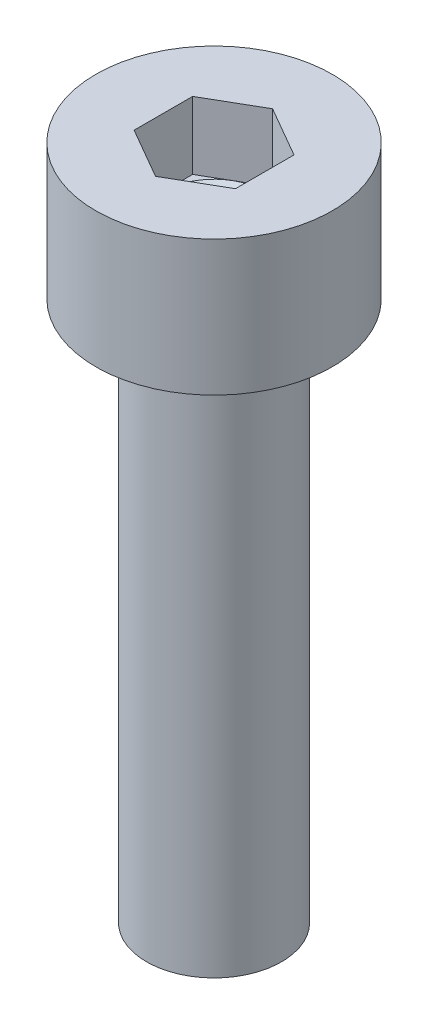
SolidWorks part; units mm, degrees
ref_plane "Front Plane" through (0, 0, 0) normal (0, 0, 1) x (1, 0, 0)
ref_plane "Top Plane" through (0, 0, 0) normal (0, 1, 0) x (1, 0, 0)
ref_plane "Right Plane" through (0, 0, 0) normal (1, 0, 0) x (0, 0, -1)
sketch "Sketch1" plane through (0, 0, 0) normal (0, 0, 1) x (1, 0, 0)
  line L0 (0, 0) -> (3.5, 0)
  line L1 (3.5, 0) -> (3.5, -4)
  line L2 (3.5, -4) -> (2, -4)
  line L3 (2, -4) -> (2, -20)
  line L4 (2, -20) -> (0, -20)
  line L5 (0, -20) -> (0, 0)
  line L7 (0, 0) -> (0, -20) construction
  dimension "CS_A" = 7
  dimension "CS_L" = 16
  dimension "CS_M" = 4
  dimension "CS_E" = 4
revolve "Revolve1" add sketch "Sketch1" angle 360 about L7
cosmetic thread "Cosmetic Thread1" parameters "CS_D_s"=3.242
sketch "Sketch2" plane through (0, 0, 0) normal (0, 0, 1) x (1, 0, 0)
  line L0 (1.5, 0) -> (1.5, -2)
  line L1 (1.5, -2) -> (0, -2.866)
  line L2 (0, -2.866) -> (0, 0)
  line L3 (0, 0) -> (1.5, 0)
  line L4 (0, 0) -> (0, -2.866) construction
  dimension "D1" = 60
  dimension "CS_B" = 3
  dimension "CS_T_s" = 2
revolve "Cut-Revolve1" cut sketch "Sketch2" angle 360 about L4
sketch "Sketch3" plane through (0, 0, 0) normal (0, 1, 0) x (1, 0, 0)
  line L1 (0, 1.7321) -> (-1.5, 0.866)
  line L2 (-1.5, 0.866) -> (-1.5, -0.866)
  line L3 (-1.5, -0.866) -> (0, -1.7321)
  line L4 (0, -1.7321) -> (1.5, -0.866)
  line L5 (1.5, -0.866) -> (1.5, 0.866)
  line L6 (1.5, 0.866) -> (0, 1.7321)
  circle A0 centre (0, 0) radius 1.5 construction
extrude "Cut-Extrude1" cut sketch "Sketch3" against normal blind 2
